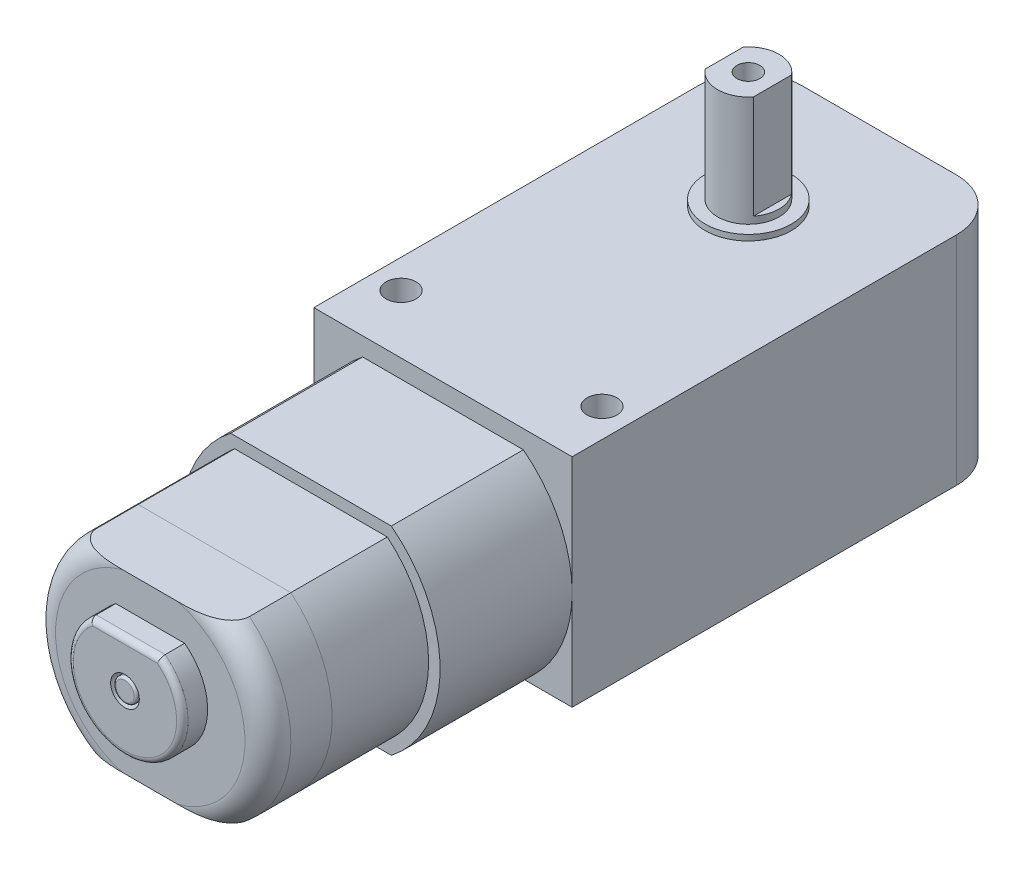
SolidWorks part; units mm, degrees
ref_plane "Front Plane" through (0, 0, 0) normal (0, 0, 1) x (1, 0, 0)
ref_plane "Top Plane" through (0, 0, 0) normal (0, 1, 0) x (1, 0, 0)
ref_plane "Right Plane" through (0, 0, 0) normal (1, 0, 0) x (0, 0, -1)
sketch "Sketch1" plane through (0, 0, 0) normal (0, 1, 0) x (1, 0, 0)
  line L1 (11.25, 19) -> (-11.25, 19)
  line L2 (11.25, 19) -> (11.25, -19)
  line L3 (11.25, -19) -> (-11.25, -19)
  line L4 (-11.25, 19) -> (-11.25, -19)
  line L5 (11.25, 19) -> (-11.25, -19) construction
  line L6 (11.25, -19) -> (-11.25, 19) construction
  point P0 (0, 0)
  dimension "D1" = 22.5
  dimension "D2" = 38
extrude "Boss-Extrude1" add sketch "Sketch1" along normal mid plane 18.9
fillet "Fillet1" radius 4.5 2 edges at (-11.25, 0, -19) (11.25, 0, -19)
sketch "Sketch2" plane through (0, 0, 19) normal (0, 0, 1) x (1, 0, 0)
  line L0 (-11.25, -9.45) -> (11.25, -9.45) construction
  line L5 (7, -9.45) -> (-7, -9.45)
  line L7 (7, 7.85) -> (-7, 7.85)
  line L9 (7, -9.45) -> (-7, 7.85) construction
  line L10 (7, 7.85) -> (-7, -9.45) construction
  line L13 (-11.25, 9.45) -> (-11.25, -9.45) construction
  arc A0 (-7, 7.85) -> (-7, -9.45) centre (-0.3224, -0.8) ccw
  arc A1 (7, 7.85) -> (7, -9.45) centre (0.3224, -0.8) cw
  point P0 (0, -0.8)
  dimension "D3" = 10.9276
  dimension "D1" = 17.3
  dimension "D2" = 14
extrude "Boss-Extrude2" add sketch "Sketch2" along normal blind 11.5
sketch "Sketch3" plane through (0, 0, 30.5) normal (0, 0, 1) x (1, 0, 0)
  line L4 (-6.6497, -8.45) -> (6.6497, -8.45)
  line L5 (6.6497, 6.85) -> (-6.6497, 6.85)
  line L6 (-6.6497, -8.45) -> (6.6497, -8.45)
  line L7 (6.6497, 6.85) -> (-6.6497, 6.85)
  arc A4 (-6.6497, 6.85) -> (-6.6497, -8.45) centre (-0.3224, -0.8) ccw
  arc A5 (6.6497, -8.45) -> (6.6497, 6.85) centre (0.3224, -0.8) ccw
  arc A6 (-6.6497, 6.85) -> (-6.6497, -8.45) centre (-0.3224, -0.8) ccw
  arc A7 (6.6497, -8.45) -> (6.6497, 6.85) centre (0.3224, -0.8) ccw
  dimension "D1" = 1
extrude "Cut-Extrude1" cut sketch "Sketch3" against normal up to surface (11.5 mm away) up to face at (0, 5.6646, 19)
sketch "Sketch4" plane through (0, 0, 0) normal (0, 1, 0) x (1, 0, 0)
  line L0 (6.75, 19) -> (-6.75, 19) construction
  line L1 (2.5, 19) -> (-2.5, 19)
  line L2 (2.5, 19) -> (2.5, 24)
  line L3 (2.5, 24) -> (-2.5, 24)
  line L4 (-2.5, 19) -> (-2.5, 24)
  line L5 (2.5, 19) -> (-2.5, 24) construction
  line L6 (2.5, 24) -> (-2.5, 19) construction
  circle A0 centre (0, 21.5) radius 1.25
  point P0 (0, 21.5)
  dimension "D3" = 2.5
  dimension "D1" = 5
  dimension "D2" = 5
extrude "Boss-Extrude3" add sketch "Sketch4" along normal mid plane 2.5 contours L4 L1 L2 L3 A0
sketch "Sketch5" plane through (0, 9.45, 0) normal (0, 1, 0) x (1, 0, 0)
  line L0 (0, 24) -> (0, 0) construction
  line L1 (2.5, 24) -> (-2.5, 24) construction
  line L2 (6.75, 19) -> (-6.75, 19) construction
  circle A0 centre (0, 7.6) radius 3.75
  dimension "D1" = 7.5
  dimension "D2" = 11.4
extrude "Boss-Extrude4" add sketch "Sketch5" along normal blind 0.5
sketch "Sketch6" plane through (0, 9.95, 0) normal (0, 1, 0) x (1, 0, 0)
  circle A0 centre (0, 7.6) radius 2.675
  dimension "D1" = 5.35
extrude "Boss-Extrude5" add sketch "Sketch6" along normal blind 9.6
sketch "Sketch7" plane through (0, 19.55, 0) normal (0, 1, 0) x (1, 0, 0)
  line L0 (-2.1, 9.257) -> (-2.1, 5.943)
  line L1 (2.1, 9.257) -> (2.1, 5.943)
  line L2 (-2.1, 7.6) -> (2.1, 7.6) construction
  circle A0 centre (0, 7.6) radius 2.675 construction
  circle A1 centre (0, 7.6) radius 2.675 construction
  arc A2 (2.1, 5.943) -> (2.1, 9.257) centre (0, 7.6) ccw
  circle A3 centre (0, 7.6) radius 2.675
  arc A4 (-2.1, 9.257) -> (-2.1, 5.943) centre (0, 7.6) ccw
  point P10 (0, 7.6)
  dimension "D2" = 4.2
  dimension "D1" = 0
extrude "Cut-Extrude4" cut sketch "Sketch7" against normal blind 9
sketch "Sketch8" plane through (0, 19.55, 0) normal (0, 1, 0) x (1, 0, 0)
  circle A0 centre (0, 7.6) radius 1
  dimension "D1" = 2
extrude "Cut-Extrude5" cut sketch "Sketch8" against normal up to surface (9 mm away) up to face at (-2.3875, 10.55, -7.6)
fillet "Fillet2" radius 0.5 2 edges at (2.5, 0, -24) (-2.5, 0, -24)
sketch "Sketch9" plane through (0, 0, 19) normal (0, 0, 1) x (1, 0, 0)
  line L2 (-6.6497, -8.45) -> (6.6497, -8.45)
  line L3 (6.6497, 6.85) -> (-6.6497, 6.85)
  line L4 (-6.6497, -8.45) -> (6.6497, -8.45)
  line L5 (6.6497, 6.85) -> (-6.6497, 6.85)
  arc A2 (-6.6497, 6.85) -> (-6.6497, -8.45) centre (-0.3224, -0.8) ccw
  arc A3 (6.6497, -8.45) -> (6.6497, 6.85) centre (0.3224, -0.8) ccw
  arc A4 (-6.6497, 6.85) -> (-6.6497, -8.45) centre (-0.3224, -0.8) ccw
  arc A5 (6.6497, -8.45) -> (6.6497, 6.85) centre (0.3224, -0.8) ccw
  dimension "D1" = 0
extrude "Boss-Extrude6" add sketch "Sketch9" along normal blind 27.7 separate body
sketch "Sketch10" plane through (0, 6.85, 0) normal (0, 1, 0) x (1, 0, 0)
  line L0 (-10.25, -38.9) -> (10.25, -38.9)
  line L1 (-10.25, -19) -> (-10.25, -46.7) construction
  line L2 (10.25, -46.7) -> (10.25, -19) construction
  line L3 (7, -30.5) -> (-7, -30.5) construction
  dimension "D1" = 8.4
split "Split1" trim tools "Sketch10" bodies to split 109 resulting bodies 110 111
sketch "Sketch11" plane through (0, 0, 46.7) normal (0, 0, 1) x (1, 0, 0)
  line L0 (-3, 4) -> (3, 4)
  line L3 (-6.6497, -8.45) -> (6.6497, -8.45)
  line L4 (6.6497, 6.85) -> (-6.6497, 6.85)
  line L5 (-6.6497, -8.45) -> (6.6497, -8.45)
  line L6 (6.6497, 6.85) -> (-6.6497, 6.85)
  arc A0 (-3, 4) -> (3, 4) centre (0, 0) ccw
  arc A3 (-6.6497, 6.85) -> (-6.6497, -8.45) centre (-0.3224, -0.8) ccw
  arc A7 (-6.6497, 6.85) -> (-6.6497, -8.45) centre (-0.3224, -0.8) ccw
  arc A9 (6.6497, -8.45) -> (6.6497, 6.85) centre (0.3224, -0.8) ccw
  arc A10 (6.6497, -8.45) -> (6.6497, 6.85) centre (0.3224, -0.8) ccw
  dimension "D1" = 10
  dimension "D2" = 9
  dimension "D3" = 0
extrude "Cut-Extrude6" cut sketch "Sketch11" against normal blind 2.2
fillet "Fillet4" radius 0.5 2 edges at (0, -5, 46.7) (0, 4, 46.7)
fillet "Fillet3" radius 2 2 edges at (-10.25, -0.8, 44.5) (10.25, -0.8, 44.5)
sketch "Sketch12" plane through (0, 0, 46.7) normal (0, 0, 1) x (1, 0, 0)
  circle A0 centre (0, 0) radius 1.25
  dimension "D1" = 2.5
extrude "Cut-Extrude7" cut sketch "Sketch12" against normal up to surface (2.2 mm away) up to face at (0, -0.5, 44.5)
sketch "Sketch13" plane through (0, 0, 44.5) normal (0, 0, 1) x (1, 0, 0)
  circle A0 centre (0, 0) radius 1
  dimension "D1" = 2
extrude "Boss-Extrude7" add sketch "Sketch13" along normal up to surface (2.2 mm away) up to face at (1.25, 0, 46.7)
fillet "Fillet5" radius 0.2 1 edges at (1, 0, 46.7)
sketch "Sketch14" plane through (0, 9.45, 0) normal (0, 1, 0) x (1, 0, 0)
  line L0 (-8.75, -13.9) -> (8.75, -13.9) construction
  line L1 (11.25, -19) -> (11.25, 14.5) construction
  line L4 (7, -19) -> (11.25, -19) construction
  circle A0 centre (-8.75, -13.9) radius 1.3
  circle A1 centre (8.75, -13.9) radius 1.3
  point P11 (0, -13.9)
  dimension "D1" = 2.6
  dimension "D2" = 2.5
  dimension "D3" = 5.1
extrude "Cut-Extrude8" cut sketch "Sketch14" against normal up to surface (18.9 mm away) up to face at (0, -9.45, 6.8136)
sketch "Sketch15" plane through (0, 19.55, 0) normal (0, 1, 0) x (1, 0, 0)
  circle A0 centre (0, 7.6) radius 2.675
  dimension "D1" = 5.35
equation "\"D2@Sketch14\"= 1.2 + (\"D1@Sketch14\"/2)"
equation "\"D3@Sketch14\"=3.8 + (\"D1@Sketch14\"/2)"
